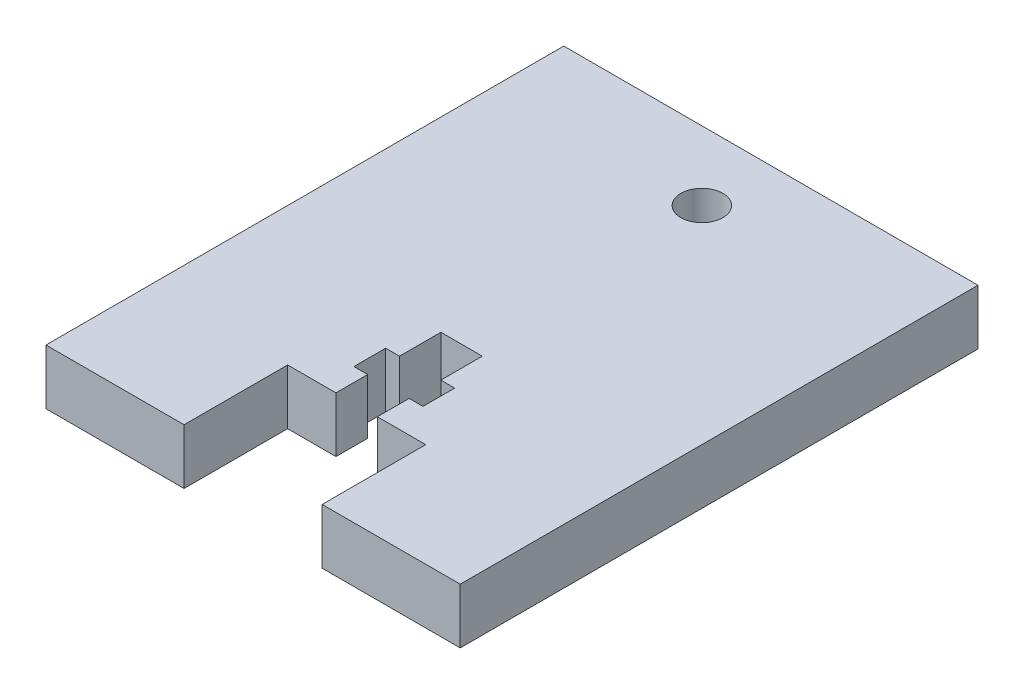
SolidWorks part; units mm, degrees
ref_plane "Front Plane" through (0, 0, 0) normal (0, 0, 1) x (1, 0, 0)
ref_plane "Top Plane" through (0, 0, 0) normal (0, 1, 0) x (1, 0, 0)
ref_plane "Right Plane" through (0, 0, 0) normal (1, 0, 0) x (0, 0, -1)
sketch "Sketch1" plane through (0, 0, 0) normal (0, 1, 0) x (1, 0, 0)
  line L0 (-10, -37) -> (-10, -22)
  line L1 (10, -37) -> (30, -37)
  line L2 (30, -37) -> (30, 38)
  line L4 (-30, -37) -> (-30, 38)
  line L5 (-5, -12.8) -> (-3, -12.8)
  line L6 (3, -12.8) -> (3, -6.8)
  line L8 (10, -37) -> (10, -22)
  line L9 (-10, -37) -> (-30, -37)
  line L10 (10, -22) -> (3, -22)
  line L11 (3, -6.8) -> (-3, -6.8)
  line L12 (3, -17.4) -> (3, -22)
  line L13 (-3, -17.4) -> (-3, -22)
  line L14 (-3, -22) -> (-10, -22)
  line L15 (5, -12.8) -> (5, -17.4)
  line L16 (5, -17.4) -> (3, -17.4)
  line L17 (-5, -17.4) -> (-3, -17.4)
  line L18 (-5, -12.8) -> (-5, -17.4)
  line L19 (-3, -6.8) -> (-3, -12.8)
  line L20 (3, -12.8) -> (5, -12.8)
  line L23 (30, 38) -> (-30, 38)
  circle A0 centre (0, 28) radius 3.05
extrude "Boss-Extrude1" add sketch "Sketch1" along normal blind 8
